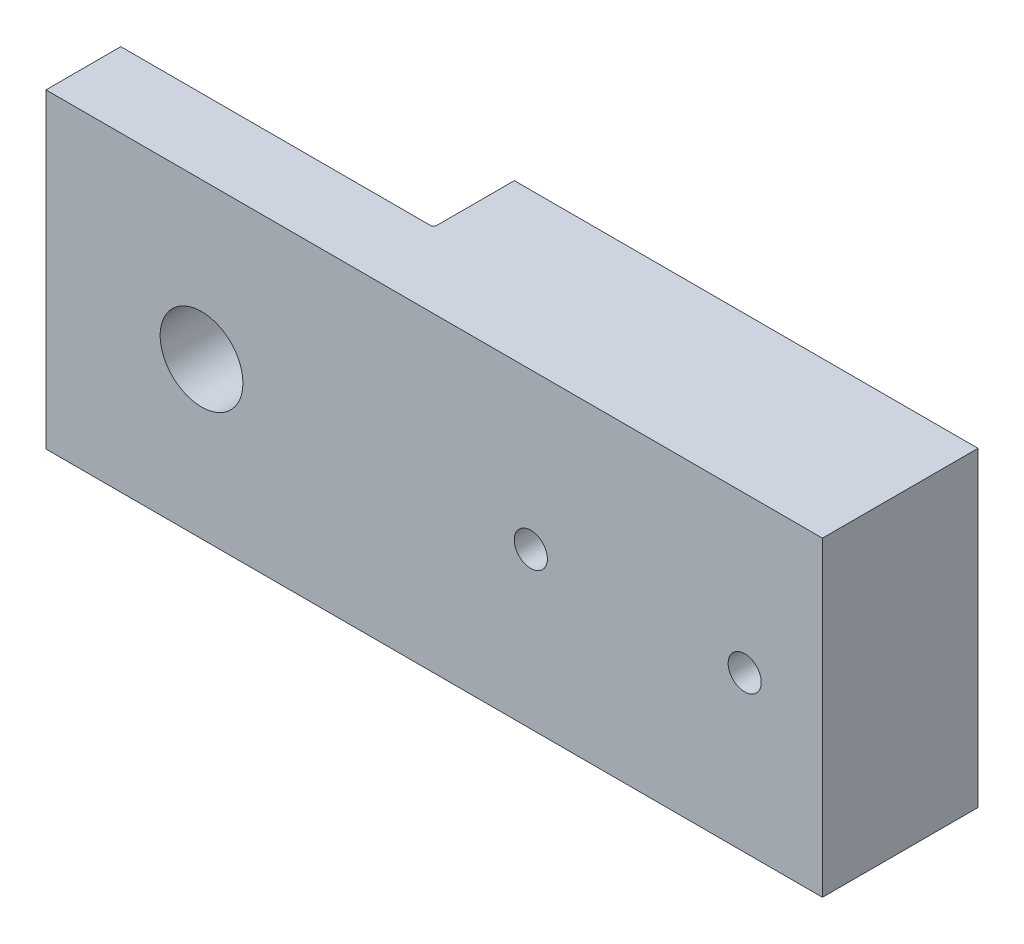
SolidWorks part; units mm, degrees
material "Rubber"
ref_plane "Front Plane" through (0, 0, 0) normal (0, 0, 1) x (1, 0, 0)
ref_plane "Top Plane" through (0, 0, 0) normal (0, 1, 0) x (1, 0, 0)
ref_plane "Right Plane" through (0, 0, 0) normal (1, 0, 0) x (0, 0, -1)
sketch "Sketch1" plane through (0, 0, 0) normal (0, 0, 1) x (1, 0, 0)
  line L16 (-882.65, 330.2) -> (31.75, 330.2) construction
  line L17 (31.75, 330.2) -> (31.75, 393.7) construction
  line L18 (31.75, 419.1) -> (53.848, 419.1)
  line L19 (-882.65, 393.7) -> (-882.65, 330.2) construction
  line L21 (-9.5504, 1019.175) -> (-9.5504, 0) construction
  line L22 (-9.5504, 0) -> (-6.3331, 0) construction
  line L23 (-6.3331, 0) -> (-6.3331, 1019.175) construction
  line L24 (-6.3331, 1019.175) -> (-9.5504, 1019.175) construction
  line L26 (9.5504, 0) -> (9.5504, 1019.175) construction
  line L29 (9.5504, 1019.175) -> (6.3331, 1019.175) construction
  line L30 (6.3331, 1019.175) -> (6.3331, 0) construction
  line L31 (6.3331, 0) -> (9.5504, 0) construction
  line L32 (-9.5504, 393.7) -> (31.75, 393.7)
  line L33 (31.75, 419.1) -> (-9.5504, 419.1)
  line L34 (-9.5504, 419.1) -> (-9.5504, 393.7)
  line L35 (31.75, 419.1) -> (31.75, 393.7)
  line L36 (53.848, 419.1) -> (53.848, 393.7)
  line L37 (53.848, 393.7) -> (31.75, 393.7)
  dimension "D1" = 25.4
  dimension "D2" = 22.098
extrude "Boss-Extrude1" add sketch "Sketch1" along normal blind 6.35
sketch "Sketch2" plane through (0, 0, 0) normal (0, 0, -1) x (-1, 0, 0)
  line L0 (-53.848, 393.7) -> (-15.748, 393.7)
  line L1 (-15.748, 393.7) -> (-15.748, 419.1)
  line L2 (-15.748, 419.1) -> (-53.848, 419.1)
  line L4 (-53.848, 419.1) -> (-53.848, 393.7)
  line L5 (-53.848, 393.7) -> (9.5504, 393.7)
  line L6 (9.5504, 393.7) -> (9.5504, 419.1)
  line L7 (9.5504, 419.1) -> (-53.848, 419.1)
  line L8 (-53.848, 419.1) -> (-53.848, 393.7)
  line L9 (-53.848, 393.7) -> (9.5504, 393.7)
  line L10 (9.5504, 393.7) -> (9.5504, 419.1)
  line L11 (9.5504, 419.1) -> (-53.848, 419.1)
  dimension "D2" = 38.1
  dimension "D1" = 0
extrude "Boss-Extrude2" add sketch "Sketch2" along normal blind 6.35
sketch "Sketch7" plane through (0, 419.1, 0) normal (0, 1, 0) x (1, 0, 0)
  line L0 (15.748, -0.2429) -> (-9.5504, -0.2429)
  line L1 (15.9909, 0) -> (15.9909, 6.35)
  line L6 (53.848, -6.35) -> (53.848, 6.35)
  line L7 (53.848, 6.35) -> (15.748, 6.35)
  line L8 (15.748, 6.35) -> (15.748, 0)
  line L9 (15.748, 0) -> (-9.5504, 0)
  line L10 (-9.5504, 0) -> (-9.5504, -6.35)
  line L11 (-9.5504, -6.35) -> (53.848, -6.35)
  line L12 (53.848, -6.35) -> (53.848, 6.35)
  line L13 (53.848, 6.35) -> (15.748, 6.35)
  line L14 (15.748, 6.35) -> (15.748, 0)
  line L15 (15.748, 0) -> (-9.5504, 0)
  line L16 (-9.5504, 0) -> (-9.5504, -6.35)
  line L17 (-9.5504, -6.35) -> (53.848, -6.35)
  arc A0 (15.748, 0.2429) -> (15.748, -0.2429) centre (15.748, 0) cw
  dimension "D2" = 0.2429
  dimension "D1" = 0
extrude "Cut-Extrude3" cut sketch "Sketch7" against normal through all
hole_wizard "Tap Drill for #6-32 Tap1" positions "Sketch8" profile "Sketch9" hole size "#6-32" standard "ANSI Inch" end condition up to next
sketch "Sketch8" plane through (0, 0, 6.35) normal (0, 0, 1) x (1, 0, 0)
  line L0 (53.848, 419.1) -> (53.848, 393.7) construction
  point P0 (47.498, 406.4)
  point P2 (30.0355, 406.4)
  point P9 (53.848, 406.4)
  dimension "D1" = 17.4625
  dimension "D2" = 6.35
sketch "Sketch9" plane through (47.498, 406.4, 6.35) normal (1, 0, 0) x (0, -1, 0)
  line L0 (0, 0) -> (0, 12.7)
  line L1 (0, 12.7) -> (1.3525, 12.7)
  line L2 (1.3525, 12.7) -> (1.3525, 0)
  line L5 (1.3525, 0) -> (0, 0)
  line L11 (0, -6.35) -> (0, 107.95) construction
  dimension "Thru Hole Dia." = 2.7051
  dimension "Thru Hole Depth" = 12.7
hole_wizard "1/4 Clearance Hole1" positions "Sketch10" profile "Sketch11" hole size "1/4" standard "ANSI Inch" end condition up to next
sketch "Sketch10" plane through (0, 0, 6.35) normal (0, 0, 1) x (1, 0, 0)
  line L0 (-9.5504, 419.1) -> (-9.5504, 393.7) construction
  point P0 (3.1496, 406.4)
  point P7 (-9.5504, 406.4)
  dimension "D1" = 12.7
sketch "Sketch11" plane through (3.1496, 406.4, 6.35) normal (1, 0, 0) x (0, -1, 0)
  line L0 (0, 0) -> (0, 6.1071)
  line L1 (0, 6.1071) -> (3.3782, 6.1071)
  line L2 (3.3782, 6.1071) -> (3.3782, 0)
  line L5 (3.3782, 0) -> (0, 0)
  line L11 (0, -6.35) -> (0, 107.95) construction
  dimension "Thru Hole Dia." = 6.7564
  dimension "Thru Hole Depth" = 6.1071
